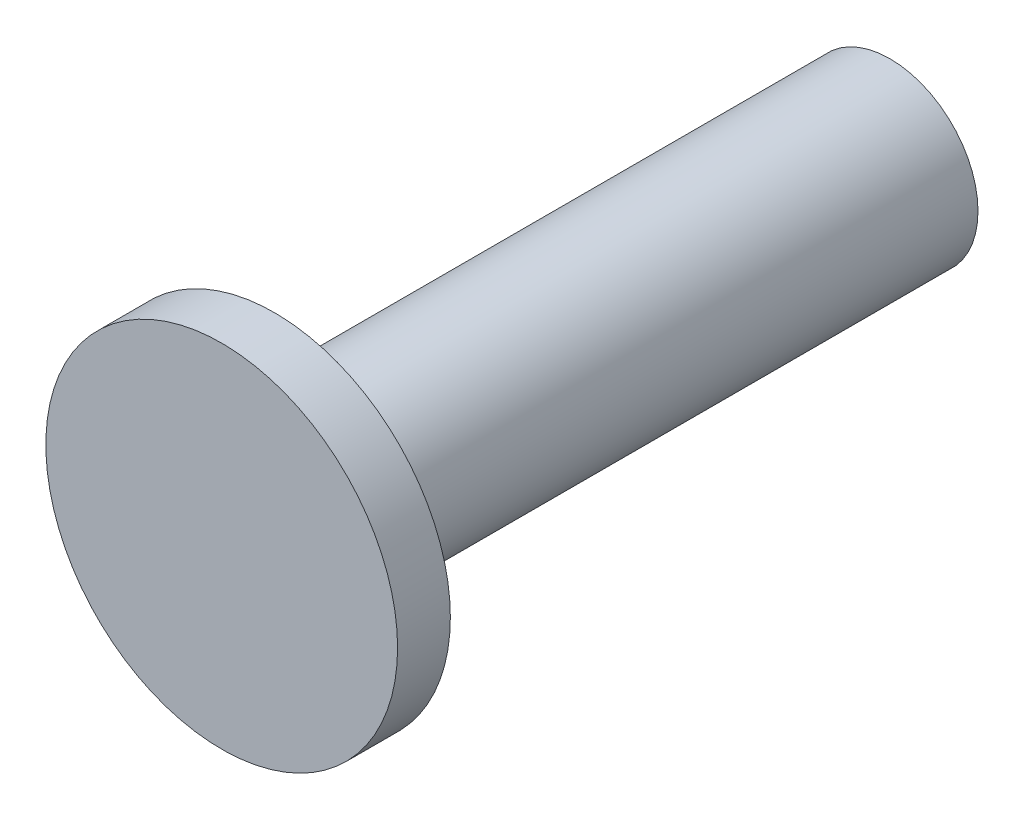
SolidWorks part; units mm, degrees
material "Acier non allié"
ref_plane "Plan de face" through (0, 0, 0) normal (0, 0, 1) x (1, 0, 0)
ref_plane "Plan de dessus" through (0, 0, 0) normal (0, 1, 0) x (1, 0, 0)
ref_plane "Plan de droite" through (0, 0, 0) normal (1, 0, 0) x (0, 0, -1)
sketch "Esquisse1" plane through (0, 0, 0) normal (0, 0, 1) x (1, 0, 0)
  circle A0 centre (0, 0) radius 5
  dimension "D1" = 10
extrude "Boss.-Extru.1" add sketch "Esquisse1" along normal blind 35
sketch "Esquisse3" plane through (0, 0, 35) normal (0, 0, 1) x (1, 0, 0)
  circle A0 centre (0, 0) radius 10
  circle A1 centre (0, 0) radius 5 construction
  dimension "D1" = 5
extrude "Boss.-Extru.2" add sketch "Esquisse3" along normal blind 3
fillet "Congé1" radius 0.5 1 edges at (5, 0, 35)
